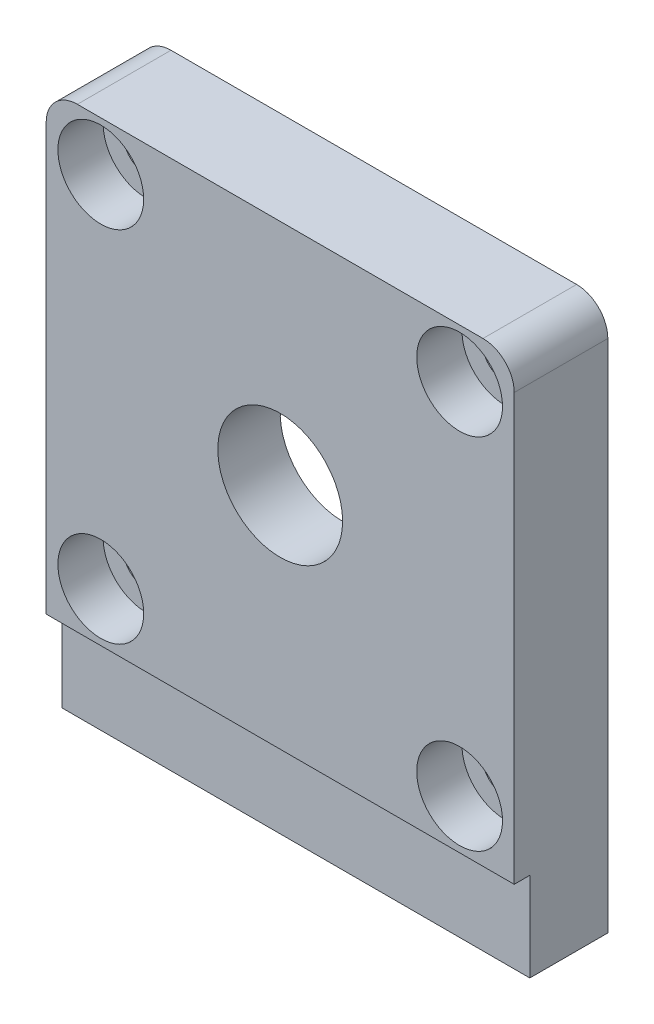
SolidWorks part; units mm, degrees
ref_plane "Спереди" through (0, 0, 0) normal (0, 0, 1) x (1, 0, 0)
ref_plane "Сверху" through (0, 0, 0) normal (0, 1, 0) x (1, 0, 0)
ref_plane "Справа" through (0, 0, 0) normal (1, 0, 0) x (0, 0, -1)
sketch "Эскиз1" plane through (-15, 0, 0) normal (-1, 0, 0) x (0, 0, 1)
  line L0 (1, 2.7) -> (1, 10.6) construction
  line L1 (0, 2.7) -> (1, 2.7) construction
  line L2 (0, 2.7) -> (0, -3) construction
  line L3 (1, 2.7) -> (1, 32)
  line L4 (0, 2.7) -> (1, 2.7)
  line L5 (0, 2.7) -> (0, -3)
  line L6 (1, 32) -> (-5, 32)
  line L7 (-5, 32) -> (-5, -3)
  line L8 (-5, -3) -> (0, -3)
  dimension "D1" = 6
  dimension "D2" = 35
extrude "Body" add sketch "Эскиз1" against normal up to surface (30 mm away)
sketch "Stepper_Fixture" plane through (0, 0, 1) normal (0, 0, 1) x (1, 0, 0)
  line L0 (0, 32) -> (0, 2.7) construction
  line L1 (15, 32) -> (-15, 32) construction
  line L2 (15, 2.7) -> (-15, 2.7) construction
  line L3 (-15, 17.35) -> (15, 17.35) construction
  line L4 (-15, 2.7) -> (-15, 32) construction
  line L5 (15, 32) -> (15, 2.7) construction
  point P13 (-11.5, 28.85)
  point P14 (11.5, 28.85)
  point P15 (-11.5, 5.85)
  point P16 (11.5, 5.85)
  dimension "D1" = 23
  dimension "D2" = 23
hole_wizard "Fixture M2.5" positions "Трехмерный эскиз1" profile "Эскиз4" counterbore size "M2.5" standard "ISO"
sketch3d "Трехмерный эскиз1"
  point P0 (-11.5, 28.85, 1)
  point P3 (11.5, 28.85, 1)
  point P6 (11.5, 5.85, 1)
  point P9 (-11.5, 5.85, 1)
sketch "Эскиз4" plane through (-11.5, 28.85, 1) normal (1, 0, 0) x (0, -1, 0)
  line L0 (0, 0) -> (0, 6.8712)
  line L1 (0, 6.8712) -> (1.45, 6)
  line L2 (1.45, 6) -> (1.45, 2.9)
  line L3 (1.45, 2.9) -> (2.75, 2.9)
  line L4 (2.75, 2.9) -> (2.75, 0)
  line L5 (2.75, 0) -> (0, 0)
  line L10 (0, 6.8712) -> (-1.45, 6) construction
  line L11 (0, -6.35) -> (0, 107.95) construction
  dimension "Диаметр отверстия" = 2.9
  dimension "Глубина отверстия" = 6
  dimension "Диаметр цековки" = 5.5
  dimension "Глубина цековки" = 2.9
  dimension "Угол заточки сверла" = 118
sketch "Эскиз5" plane through (0, 0, 1) normal (0, 0, 1) x (1, 0, 0)
  line L0 (-15, 17.35) -> (15, 17.35) construction
  line L1 (0, 32) -> (0, 2.7) construction
  line L2 (-15, 17.35) -> (15, 17.35) construction
  line L3 (0, 32) -> (0, 2.7) construction
  circle A0 centre (0, 17.35) radius 4
  dimension "D1" = 8
extrude "Вырез-Вытянуть1" cut sketch "Эскиз5" against normal up to surface (6 mm away) up to face at (-11.5, 30.3, -5)
sketch "Эскиз6" plane through (0, 0, -5) normal (0, 0, -1) x (-1, 0, 0)
  circle A0 centre (0, 17.35) radius 11
  dimension "D1" = 22
extrude "Вырез-Вытянуть2" cut sketch "Эскиз6" against normal blind 2
fillet "Скругление1" radius 2 2 edges at (15, 32, -2) (-15, 32, -2)
